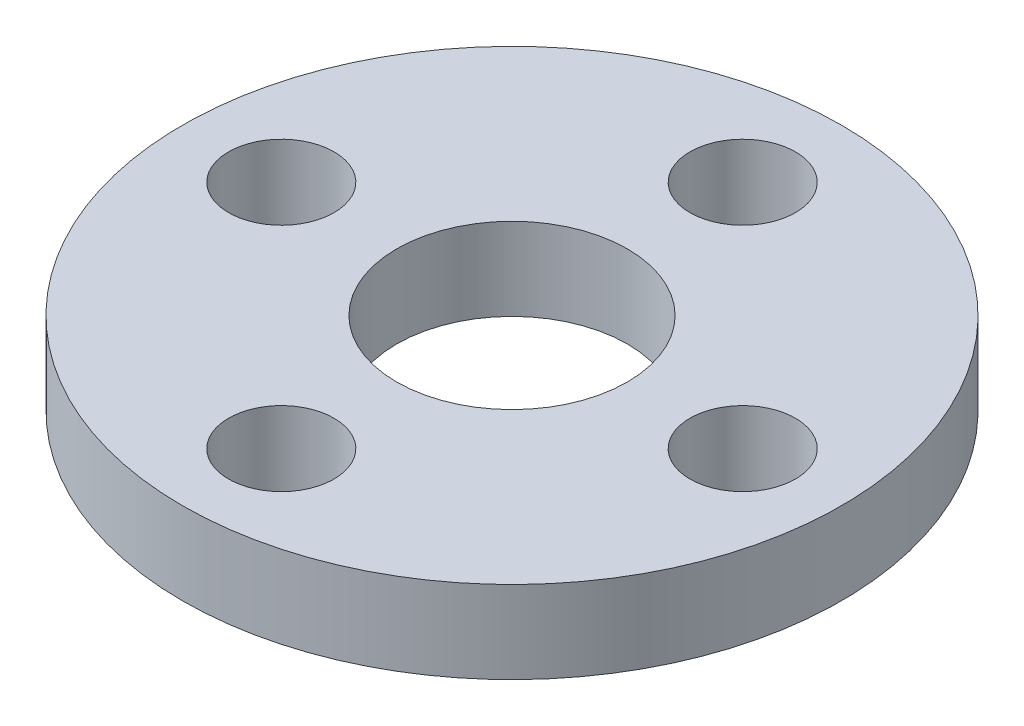
SolidWorks part; units mm, degrees
material "聚脂树脂"
ref_plane "前视基准面" through (0, 0, 0) normal (0, 0, 1) x (1, 0, 0)
ref_plane "上视基准面" through (0, 0, 0) normal (0, 1, 0) x (1, 0, 0)
ref_plane "右视基准面" through (0, 0, 0) normal (1, 0, 0) x (0, 0, -1)
other "Configuration Table"
sketch "草图1" plane through (0, 0, 0) normal (0, 1, 0) x (1, 0, 0)
  line L0 (0, 0) -> (0, 17.1458) construction
  line L1 (0, 0) -> (21.0507, 0) construction
  circle A0 centre (0, 0) radius 10
  circle A1 centre (0, 7) radius 1.6
  circle A2 centre (7, 0) radius 1.6
  circle A3 centre (0, 0) radius 3.5
  circle A4 centre (0, -7) radius 1.6
  circle A5 centre (-7, 0) radius 1.6
  dimension "D1" = 20
  dimension "D2" = 3.2
  dimension "D3" = 3.2
  dimension "D4" = 7
  dimension "D5" = 7
  dimension "D6" = 7
extrude "凸台-拉伸1" add sketch "草图1" along normal blind 2.5
